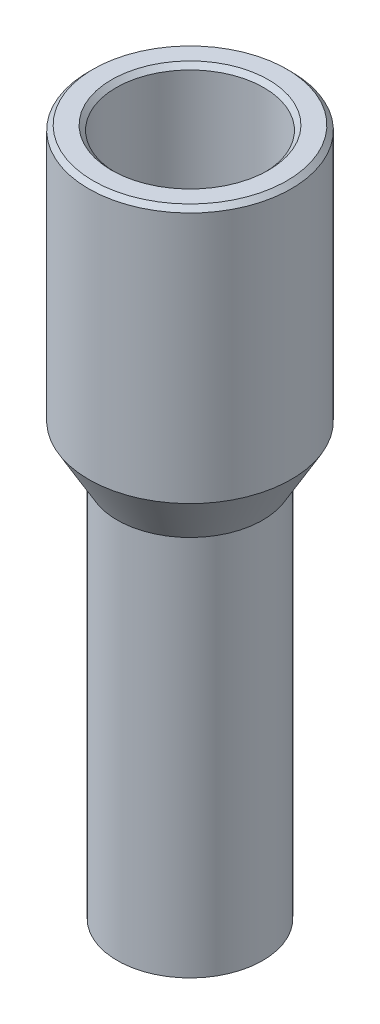
SolidWorks part; units mm, degrees
ref_plane "Front Plane" through (0, 0, 0) normal (0, 0, 1) x (1, 0, 0)
ref_plane "Top Plane" through (0, 0, 0) normal (0, 1, 0) x (1, 0, 0)
ref_plane "Right Plane" through (0, 0, 0) normal (1, 0, 0) x (0, 0, -1)
sketch "Sketch1" plane through (0, 0, 0) normal (0, 0, 1) x (1, 0, 0)
  line L0 (0, 0) -> (0, 40)
  line L1 (0, 40) -> (6.45, 40)
  line L2 (6.45, 40) -> (6.45, 60)
  line L3 (6.45, 60) -> (8.85, 60)
  line L4 (8.85, 60) -> (8.85, 37.6286)
  line L5 (8.85, 37.6286) -> (6.35, 33.2985)
  line L6 (6.35, 33.2985) -> (6.35, 0)
  line L7 (6.35, 0) -> (0, 0)
  circle A0 centre (0, 40) radius 8.85 construction
  dimension "D1" = 6.45
  dimension "D2" = 6.35
  dimension "D3" = 40
  dimension "D4" = 20
  dimension "D5" = 2.4
  dimension "D6" = 30
revolve "Revolve1" add sketch "Sketch1" angle 360 about L0
chamfer "Chamfer1" distance 0.4 angle 45 2 edges at (0, 60, -8.85) (0, 60, -6.45)
